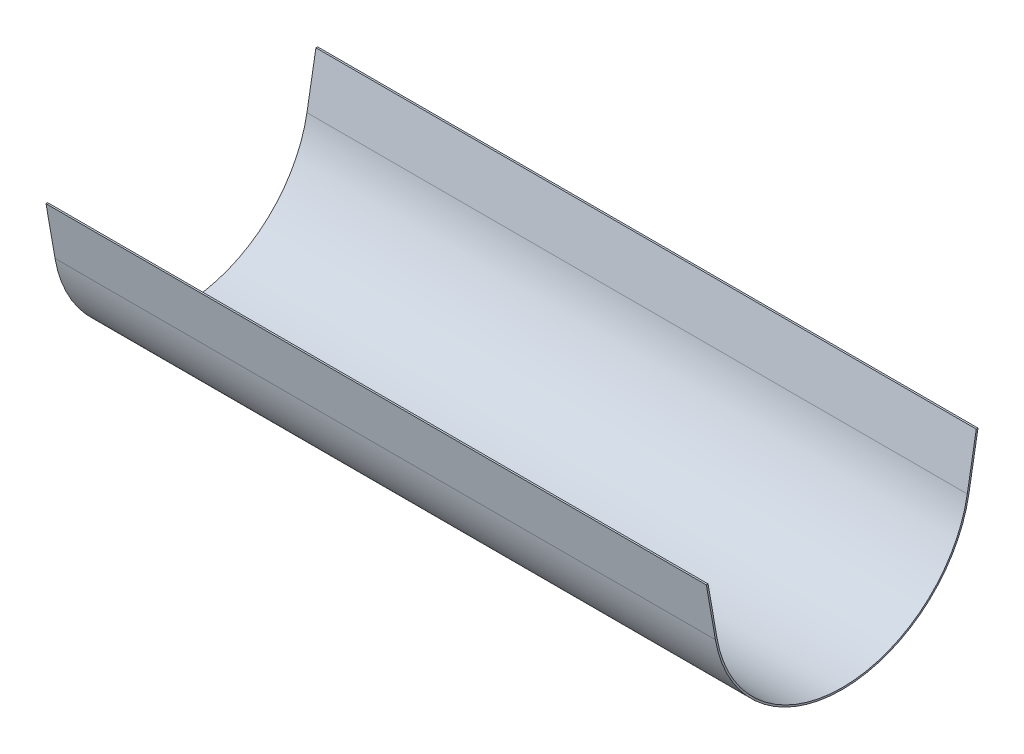
SolidWorks part; units mm, degrees
material "Silicon Rubber"
ref_plane "Front Plane" through (0, 0, 0) normal (0, 0, 1) x (1, 0, 0)
ref_plane "Top Plane" through (0, 0, 0) normal (0, 1, 0) x (1, 0, 0)
ref_plane "Right Plane" through (0, 0, 0) normal (1, 0, 0) x (0, 0, -1)
sketch "Sketch1" plane through (0, 0, 0) normal (1, 0, 0) x (0, 0, -1)
  line L0 (0, 0) -> (50000, 0) construction
  line L3 (-80.21, 0) -> (-74.8777, -30.6829)
  line L4 (80.21, 0) -> (74.8777, -30.6829)
  line L5 (-79.195, 0) -> (-73.8924, -30.5117)
  line L6 (79.195, 0) -> (73.8924, -30.5117)
  line L7 (-80.21, 0) -> (-79.195, 0)
  line L8 (-79.2248, 0.1712) -> (-73.8924, -30.5117) construction
  line L9 (80.21, 0) -> (79.195, 0)
  line L10 (79.2248, 0.1712) -> (73.8924, -30.5117) construction
  arc A0 (-74.8777, -30.6829) -> (74.8777, -30.6829) centre (0, -17.67) ccw
  arc A1 (-73.8924, -30.5117) -> (73.8924, -30.5117) centre (0, -17.67) ccw
  circle A2 centre (0, -17.67) radius 75 construction
  point P21 (0, 0)
  dimension "D4" = 17.67
  dimension "D3" = 75
  dimension "D6" = 150
  dimension "D2" = 160.42
  dimension "D1" = 1
extrude "Boss-Extrude1" add sketch "Sketch1" along normal mid plane 390
